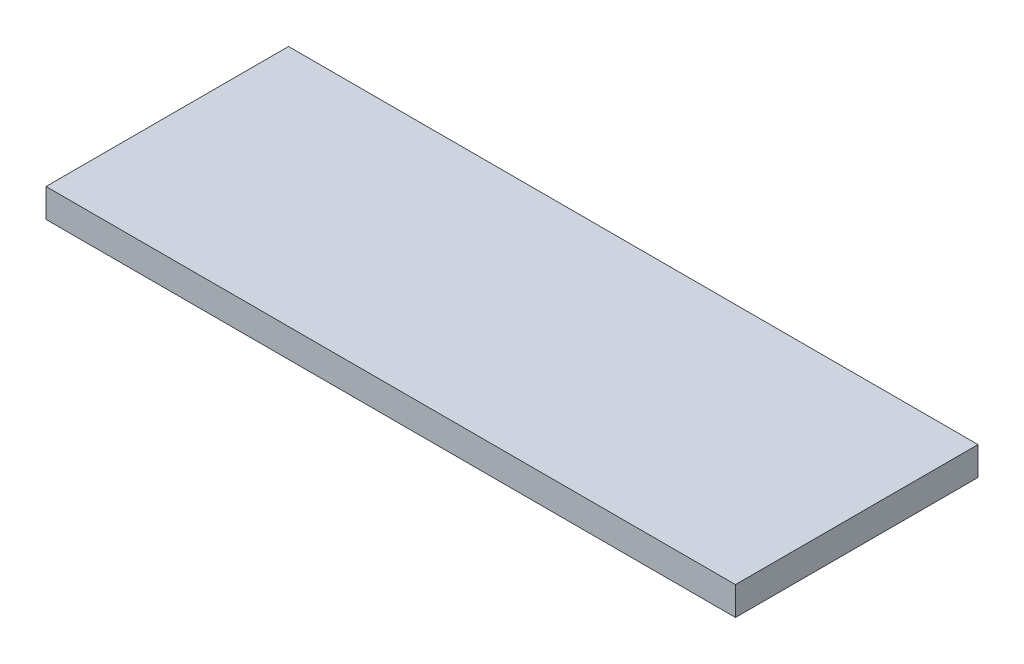
SolidWorks part; units mm, degrees
ref_plane "Спереди" through (0, 0, 0) normal (0, 0, 1) x (1, 0, 0)
ref_plane "Сверху" through (0, 0, 0) normal (0, 1, 0) x (1, 0, 0)
ref_plane "Справа" through (0, 0, 0) normal (1, 0, 0) x (0, 0, -1)
sketch "Эскиз1" plane through (0, 0, 0) normal (0, 1, 0) x (1, 0, 0)
  line L1 (0, 0) -> (72.5, 0)
  line L2 (0, 0) -> (0, -25.5)
  line L3 (0, -25.5) -> (72.5, -25.5)
  line L4 (72.5, 0) -> (72.5, -25.5)
  dimension "D1" = 25.5
  dimension "D2" = 72.5
extrude "Бобышка-Вытянуть1" add sketch "Эскиз1" along normal blind 3
